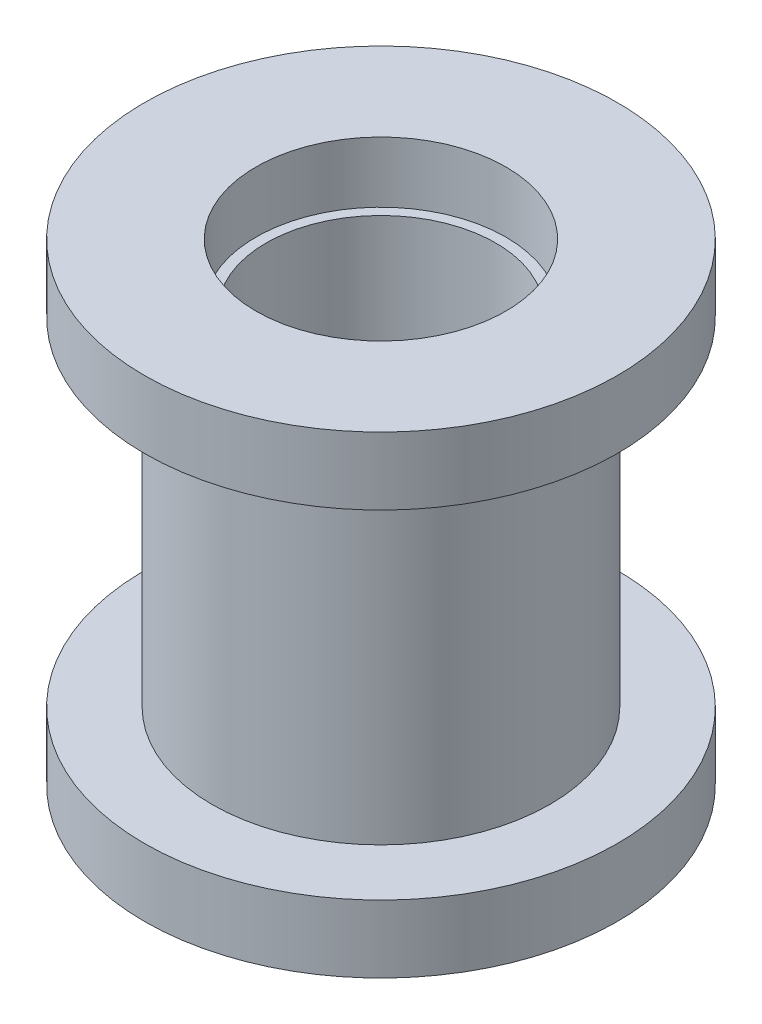
SolidWorks part; units mm, degrees
ref_plane "前视基准面" through (0, 0, 0) normal (0, 0, 1) x (1, 0, 0)
ref_plane "上视基准面" through (0, 0, 0) normal (0, 1, 0) x (1, 0, 0)
ref_plane "右视基准面" through (0, 0, 0) normal (1, 0, 0) x (0, 0, -1)
sketch "草图1" plane through (0, 0, 0) normal (0, 1, 0) x (1, 0, 0)
  line L0 (-59.8836, 0) -> (53.5136, 0) construction
  line L1 (0, 79.8453) -> (0, -44.8917) construction
  circle A0 centre (0, 0) radius 35
extrude "凸台-拉伸1" add sketch "草图1" along normal blind 10
ref_plane "基准面1" through (0, 10, 0) normal (0, 1, 0) x (1, 0, 0)
sketch "草图5" plane through (0, 10, 0) normal (0, 1, 0) x (1, 0, 0)
  circle A0 centre (0, 0) radius 25
extrude "凸台-拉伸2" add sketch "草图5" along normal blind 50
ref_plane "基准面2" through (0, 60, 0) normal (0, 1, 0) x (1, 0, 0)
sketch "草图6" plane through (0, 60, 0) normal (0, 1, 0) x (1, 0, 0)
  circle A0 centre (0, 0) radius 35
extrude "凸台-拉伸3" add sketch "草图6" along normal blind 10
ref_plane "基准面3" through (0, 70, 0) normal (0, 1, 0) x (1, 0, 0)
sketch "草图7" plane through (0, 70, 0) normal (0, 1, 0) x (1, 0, 0)
  circle A0 centre (0, 0) radius 18.5
extrude "切除-拉伸1" cut sketch "草图7" against normal blind 9
ref_plane "基准面4" through (0, 61, 0) normal (0, 1, 0) x (1, 0, 0)
sketch "草图8" plane through (0, 61, 0) normal (0, 1, 0) x (1, 0, 0)
  circle A0 centre (0, 0) radius 17
extrude "切除-拉伸2" cut sketch "草图8" against normal blind 52
ref_plane "基准面5" through (0, 9, 0) normal (0, 1, 0) x (1, 0, 0)
sketch "草图9" plane through (0, 9, 0) normal (0, 1, 0) x (1, 0, 0)
  circle A0 centre (0, 0) radius 18.5
extrude "切除-拉伸3" cut sketch "草图9" against normal through all
